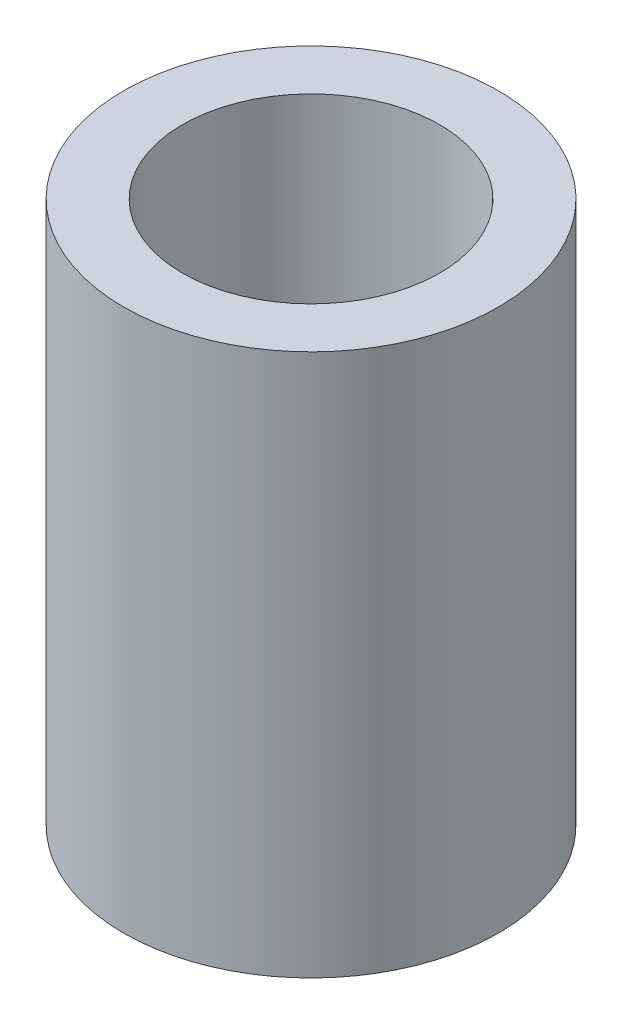
SolidWorks part; units mm, degrees
material "Rubber"
ref_plane "Front Plane" through (0, 0, 0) normal (0, 0, 1) x (1, 0, 0)
ref_plane "Top Plane" through (0, 0, 0) normal (0, 1, 0) x (1, 0, 0)
ref_plane "Right Plane" through (0, 0, 0) normal (1, 0, 0) x (0, 0, -1)
sketch "Sketch1" plane through (0, 0, 0) normal (0, 1, 0) x (1, 0, 0)
  circle A0 centre (0, 0) radius 6.025
  circle A1 centre (0, 0) radius 8.775
extrude "Boss-Extrude1" add sketch "Sketch1" along normal blind 25.4
